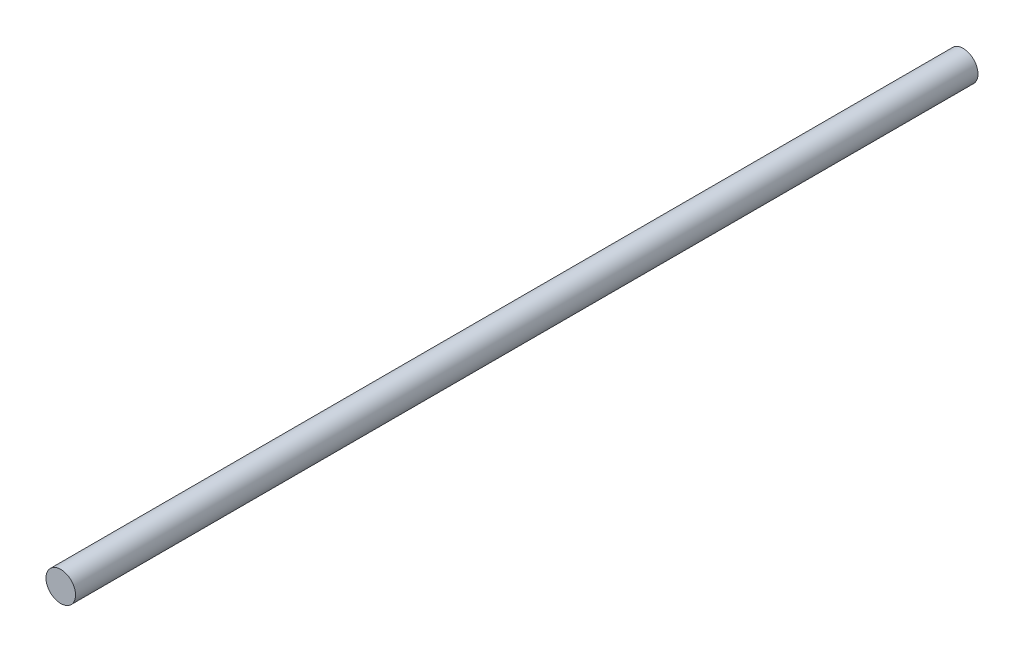
SolidWorks part; units mm, degrees
material "Простая углеродистая сталь"
ref_plane "Спереди" through (0, 0, 0) normal (0, 0, 1) x (1, 0, 0)
ref_plane "Сверху" through (0, 0, 0) normal (0, 1, 0) x (1, 0, 0)
ref_plane "Справа" through (0, 0, 0) normal (1, 0, 0) x (0, 0, -1)
sketch "Эскиз1" plane through (0, 0, 0) normal (0, 0, 1) x (1, 0, 0)
  circle A0 centre (0, 0) radius 3
  dimension "D1" = 6
extrude "База" add sketch "Эскиз1" along normal mid plane 183
